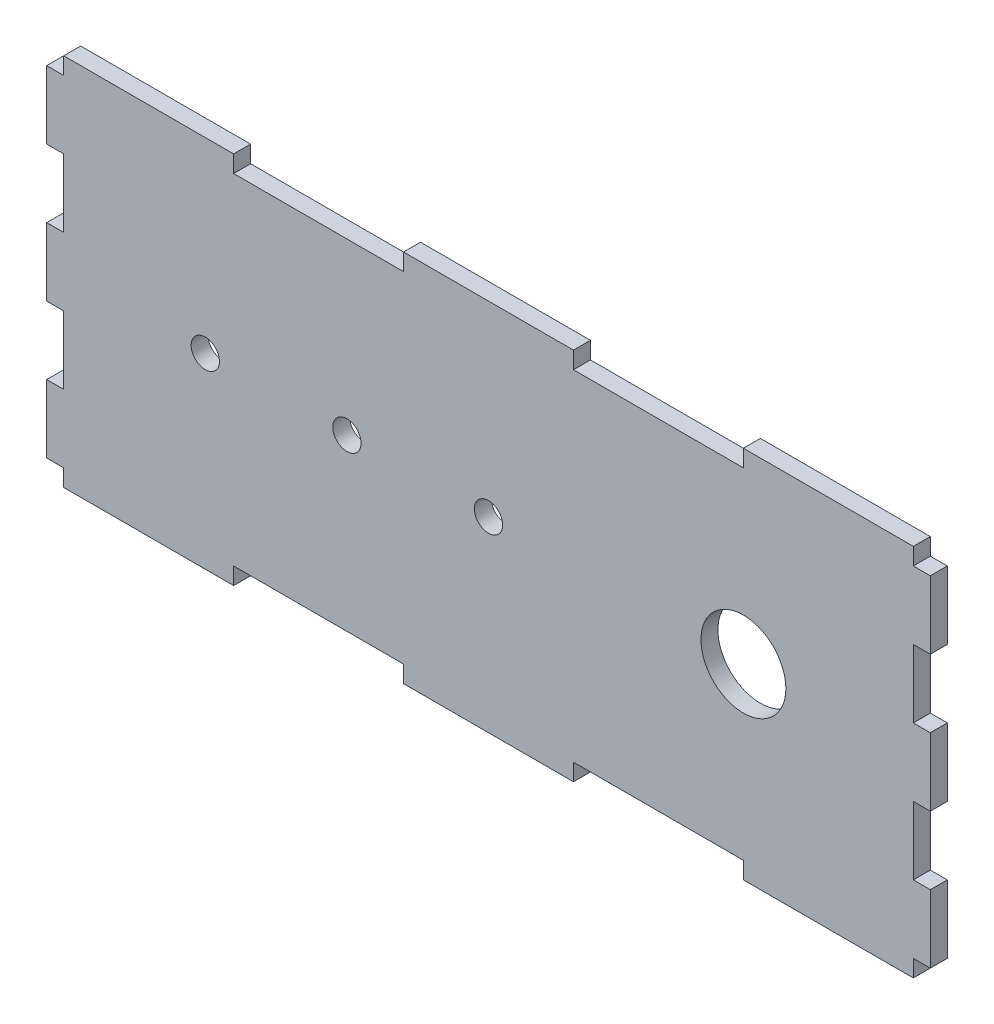
SolidWorks part; units mm, degrees
material "Pinho"
ref_plane "Plano frontal" through (0, 0, 0) normal (0, 0, 1) x (1, 0, 0)
ref_plane "Plano superior" through (0, 0, 0) normal (0, 1, 0) x (1, 0, 0)
ref_plane "Plano direito" through (0, 0, 0) normal (1, 0, 0) x (0, 0, -1)
sketch "Esboço1" plane through (0, 0, 0) normal (0, 0, 1) x (1, 0, 0)
  line L0 (-82.2996, 0) -> (73.7004, 0) construction
  line L1 (40.7004, -30) -> (10.7004, -30)
  line L2 (70.7004, -18) -> (70.7004, -6)
  line L3 (40.7004, 30) -> (10.7004, 30)
  line L4 (-79.2996, -18) -> (-79.2996, -6)
  line L5 (70.7004, 6) -> (70.7004, 18)
  line L6 (-19.2996, 30) -> (-49.2996, 30)
  line L7 (-79.2996, 30) -> (-82.2996, 30)
  line L9 (-79.2996, 18) -> (-82.2996, 18)
  line L10 (-82.2996, 30) -> (-82.2996, 18)
  line L11 (-79.2996, -30) -> (-82.2996, -30)
  line L13 (-79.2996, -18) -> (-82.2996, -18)
  line L14 (-82.2996, -30) -> (-82.2996, -18)
  line L15 (-4.2996, 33) -> (-4.2996, -33) construction
  line L16 (-79.2996, 6) -> (-79.2996, 18)
  line L17 (-82.2996, -6) -> (-79.2996, -6)
  line L18 (-82.2996, -6) -> (-82.2996, 6)
  line L19 (-82.2996, 6) -> (-79.2996, 6)
  line L20 (70.7004, -6) -> (73.7004, -6)
  line L22 (70.7004, 6) -> (73.7004, 6)
  line L23 (73.7004, -6) -> (73.7004, 6)
  line L25 (-79.2996, 30) -> (-79.2996, 33)
  line L26 (70.7004, 30) -> (73.7004, 30)
  line L28 (70.7004, 18) -> (73.7004, 18)
  line L29 (73.7004, 30) -> (73.7004, 18)
  line L30 (70.7004, -30) -> (73.7004, -30)
  line L32 (70.7004, -18) -> (73.7004, -18)
  line L33 (73.7004, -30) -> (73.7004, -18)
  line L34 (-79.2996, 33) -> (-49.2996, 33)
  line L35 (-49.2996, 30) -> (-49.2996, 33)
  line L37 (70.7004, 30) -> (70.7004, 33)
  line L38 (70.7004, 33) -> (40.7004, 33)
  line L39 (40.7004, 30) -> (40.7004, 33)
  line L41 (-19.2996, 30) -> (-19.2996, 33)
  line L42 (-19.2996, 33) -> (10.7004, 33)
  line L43 (10.7004, 30) -> (10.7004, 33)
  line L44 (-19.2996, -30) -> (-49.2996, -30)
  line L46 (-19.2996, -30) -> (-19.2996, -33)
  line L47 (-19.2996, -33) -> (10.7004, -33)
  line L48 (10.7004, -30) -> (10.7004, -33)
  line L52 (-79.2996, -30) -> (-79.2996, -33)
  line L53 (-79.2996, -33) -> (-49.2996, -33)
  line L54 (-49.2996, -30) -> (-49.2996, -33)
  line L56 (70.7004, -30) -> (70.7004, -33)
  line L57 (70.7004, -33) -> (40.7004, -33)
  line L58 (40.7004, -30) -> (40.7004, -33)
  circle A0 centre (-54.2996, 0) radius 2.5
  circle A1 centre (-29.2996, 0) radius 2.5
  circle A2 centre (-4.2996, 0) radius 2.5
  circle A3 centre (40.7004, 0) radius 7.5
  point P0 (0, 0)
  dimension "D28" = 5
  dimension "D29" = 5
  dimension "D30" = 5
  dimension "D33" = 15
  dimension "D1" = 60
  dimension "D2" = 150
  dimension "D3" = 3
  dimension "D4" = 12
  dimension "D5" = 12
  dimension "D6" = 12
  dimension "D7" = 3
  dimension "D8" = 3
  dimension "D9" = 6
  dimension "D10" = 12
  dimension "D11" = 3
  dimension "D12" = 12
  dimension "D13" = 3
  dimension "D14" = 12
  dimension "D15" = 3
  dimension "D16" = 30
  dimension "D17" = 30
  dimension "D18" = 30
  dimension "D19" = 3
  dimension "D20" = 3
  dimension "D21" = 3
  dimension "D22" = 30
  dimension "D23" = 30
  dimension "D24" = 30
  dimension "D25" = 3
  dimension "D26" = 3
  dimension "D27" = 3
  dimension "D31" = 25
  dimension "D32" = 25
  dimension "D34" = 30
  dimension "D35" = 25
extrude "Ressalto-extrusão1" add sketch "Esboço1" along normal blind 3
